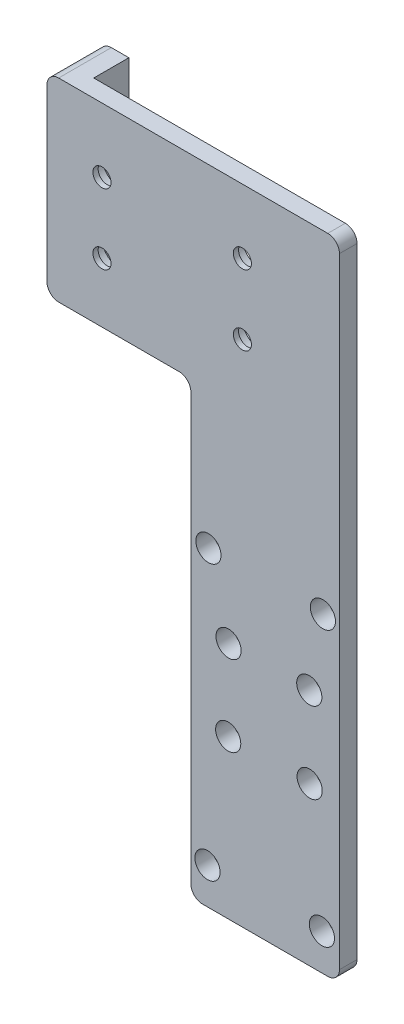
SolidWorks part; units mm, degrees
material "ABS"
ref_plane "Plan de face" through (0, 0, 0) normal (0, 0, 1) x (1, 0, 0)
ref_plane "Plan de dessus" through (0, 0, 0) normal (0, 1, 0) x (1, 0, 0)
ref_plane "Plan de droite" through (0, 0, 0) normal (1, 0, 0) x (0, 0, -1)
sketch "Esquisse1" plane through (0, 0, 0) normal (0, 0, 1) x (1, 0, 0)
  line L1 (0, 0) -> (26.6382, 0)
  line L2 (1.2382, -33.1762) -> (1.2382, -109.993)
  line L3 (1.2382, -109.993) -> (26.6382, -109.993)
  line L4 (26.6382, 0) -> (26.6382, -109.993)
  line L9 (1.2382, -33.1762) -> (-23.3618, -33.1762)
  line L11 (0, 0) -> (-23.3618, 0)
  line L12 (-23.3618, -33.1762) -> (-23.3618, 0)
  point P4 (-23.3618, -16.5881)
  dimension "D1" = 110
  dimension "D2" = 25.4
  dimension "D3" = 50
extrude "Boss.-Extru.1" add sketch "Esquisse1" along normal blind 3
hole_wizard "Dégagement #61" positions "Esquisse3" profile "Esquisse4" hole size "#6" standard "Ansi Inch" end condition up to next
sketch "Esquisse3" plane through (0, 0, 3) normal (0, 0, 1) x (1, 0, 0)
  line L0 (26.6382, -109.993) -> (26.6382, 0) construction
  line L1 (1.2382, -109.993) -> (26.6382, -109.993) construction
  point P0 (21.4763, -69.193)
  point P2 (7.6763, -69.193)
  point P4 (7.6172, -82.993)
  point P6 (21.5382, -82.993)
  dimension "D1" = 19.558
  dimension "D2" = 19.56
  dimension "D3" = 13.8
  dimension "D4" = 13.8
  dimension "D5" = 13.8
  dimension "D6" = 27
  dimension "D7" = 5.1
  dimension "D8" = 27
sketch "Esquisse4" plane through (21.4763, -69.193, 3) normal (1, 0, 0) x (0, -1, 0)
  line L0 (0, 0) -> (0, 3)
  line L1 (0, 3) -> (2.1526, 3)
  line L2 (2.1526, 3) -> (2.1526, 0)
  line L5 (2.1526, 0) -> (0, 0)
  line L11 (0, -6.35) -> (0, 107.95) construction
  dimension "Diamètre du perçage jusqu'au prochain" = 4.3053
  dimension "Profondeur du perçage jusqu'au prochain" = 3
hole_wizard "Chambrage pour vis à tête ronde bombée M2.51" positions "Esquisse5" profile "Esquisse6" counterbore size "M2.5" standard "Ansi Metric" end condition up to next
sketch "Esquisse5" plane through (0, 0, 0) normal (0, 0, -1) x (-1, 0, 0)
  line L0 (-26.6382, 0) -> (23.3618, 0) construction
  line L1 (23.3618, 0) -> (23.3618, -33.1762) construction
  point P0 (13.9618, -23)
  point P2 (13.9618, -11)
  point P4 (-10.0382, -11)
  point P6 (-10.0382, -23)
  dimension "D1" = 11
  dimension "D2" = 9.4
  dimension "D3" = 12
  dimension "D4" = 24
  dimension "D5" = 12
  dimension "D6" = 24
  dimension "D7" = 11
  dimension "D8" = 9.4
sketch "Esquisse6" plane through (-13.9618, -23, 0) normal (1, 0, 0) x (0, 1, 0)
  line L0 (0, 0) -> (0, 3)
  line L1 (0, 3) -> (1.55, 3)
  line L3 (1.55, 3) -> (1.55, 2.1)
  line L4 (1.55, 2.1) -> (3, 2.1)
  line L5 (3, 2.1) -> (3, 0)
  line L7 (3, 0) -> (0, 0)
  line L11 (0, -6.35) -> (0, 107.95) construction
  dimension "Diamètre du perçage jusqu'au prochain" = 3.1
  dimension "Profondeur du perçage jusqu'au prochain" = 3
  dimension "Diamètre du chambrage" = 6
  dimension "Profondeur du chambrage" = 2.1
sketch "Esquisse7" plane through (0, 0, 0) normal (0, 0, -1) x (-1, 0, 0)
  line L0 (-11.6382, -63.1762) -> (-11.6382, -33.1762)
  line L2 (-16.6382, -28.1762) -> (-16.6382, -63.1762)
  line L3 (-16.6382, -63.1762) -> (-11.6382, -63.1762)
  line L9 (-11.6382, -33.1762) -> (23.3618, -33.1762)
  line L11 (-16.6382, -28.1762) -> (18.3618, -28.1762)
  line L14 (23.3618, -33.1762) -> (23.3618, 0)
  line L15 (23.3618, 0) -> (18.3618, 0)
  line L16 (18.3618, -28.1762) -> (18.3618, 0)
  line L21 (-16.6382, -89.993) -> (-11.6382, -89.993)
  line L22 (-16.6382, -89.993) -> (-16.6382, -109.993)
  line L23 (-16.6382, -109.993) -> (-11.6382, -109.993)
  line L24 (-11.6382, -89.993) -> (-11.6382, -109.993)
  line L29 (-26.6382, -109.993) -> (-26.6382, 0) construction
  line L30 (-1.2382, -109.993) -> (-26.6382, -109.993) construction
  dimension "D1" = 5
  dimension "D2" = 5
  dimension "D3" = 5
  dimension "D4" = 10
  dimension "D5" = 5
  dimension "D6" = 35
  dimension "D7" = 20
  dimension "D8" = 10
  dimension "D9" = 0
extrude "Boss.-Extru.2" add sketch "Esquisse7" along normal blind 6
sketch "Esquisse8" plane through (11.6382, 0, 0) normal (-1, 0, 0) x (0, 0, 1)
  line L0 (-6, -63.1762) -> (-6, -33.1762) construction
  line L1 (-4, -46.1762) -> (-2, -46.1762)
  line L2 (-4, -46.1762) -> (-4, -52.1762)
  line L3 (-4, -52.1762) -> (-2, -52.1762)
  line L4 (-2, -46.1762) -> (-2, -52.1762)
  line L5 (-6, -63.1762) -> (0, -63.1762) construction
  dimension "D1" = 6
  dimension "D2" = 2
  dimension "D3" = 2
  dimension "D4" = 11
extrude "Enlèv. mat.-Extru.1" cut sketch "Esquisse8" against normal up to next
sketch "Esquisse9" plane through (0, -33.1762, 0) normal (0, -1, 0) x (1, 0, 0)
  line L0 (11.6382, -6) -> (-23.3618, -6) construction
  line L1 (-0.3618, -4) -> (-6.3618, -4)
  line L2 (-0.3618, -4) -> (-0.3618, -2)
  line L3 (-0.3618, -2) -> (-6.3618, -2)
  line L4 (-6.3618, -4) -> (-6.3618, -2)
  line L5 (11.6382, -6) -> (11.6382, 0) construction
  dimension "D1" = 6
  dimension "D2" = 2
  dimension "D3" = 2
  dimension "D4" = 12
extrude "Enlèv. mat.-Extru.2" cut sketch "Esquisse9" against normal up to next
sketch "Esquisse10" plane through (-23.3618, 0, 0) normal (-1, 0, 0) x (0, 0, 1)
  line L0 (-6, -33.1762) -> (-6, 0) construction
  line L1 (-4, -12.1762) -> (-2, -12.1762)
  line L2 (-4, -12.1762) -> (-4, -18.1762)
  line L3 (-4, -18.1762) -> (-2, -18.1762)
  line L4 (-2, -12.1762) -> (-2, -18.1762)
  line L5 (3, -33.1762) -> (-6, -33.1762) construction
  dimension "D1" = 6
  dimension "D2" = 2
  dimension "D3" = 2
  dimension "D4" = 15
extrude "Enlèv. mat.-Extru.3" cut sketch "Esquisse10" against normal up to next
fillet "Congé1" radius 2 9 edges at (-18.3618, -28.1762, -3) (16.6382, -28.1762, -3) (11.6382, -33.1762, -3) (1.2382, -33.1762, 1.5) (26.6382, -109.993, 1.5) (1.2382, -109.993, 1.5) (-23.3618, 0, -1.5) (26.6382, 0, 1.5) (-23.3618, -33.1762, -1.5)
hole_wizard "Dégagement #65" positions "Esquisse11" profile "Esquisse12" hole size "#6" standard "Ansi Inch" end condition through all
sketch "Esquisse11" plane through (0, 0, 0) normal (0, 0, -1) x (-1, 0, 0)
  line L0 (-26.6382, -107.993) -> (-26.6382, -2) construction
  line L1 (-16.6382, -109.993) -> (-24.6382, -109.993) construction
  line L2 (-3.2382, -109.993) -> (-11.6382, -109.993) construction
  point P0 (-23.6382, -103.793)
  point P2 (-4.0782, -103.793)
  dimension "D1" = 3
  dimension "D2" = 6.2
  dimension "D3" = 19.56
  dimension "D4" = 6.2
sketch "Esquisse12" plane through (23.6382, -103.793, 0) normal (1, 0, 0) x (0, 1, 0)
  line L0 (0, 0) -> (0, 3)
  line L1 (0, 3) -> (2.1526, 3)
  line L2 (2.1526, 3) -> (2.1526, 0)
  line L5 (2.1526, 0) -> (0, 0)
  line L11 (0, -6.35) -> (0, 107.95) construction
  dimension "Diamètre du perçage jusqu'au prochain" = 4.3053
  dimension "Profondeur du perçage jusqu'au prochain" = 3
hole_wizard "Dégagement #64" positions "Esquisse13" profile "Esquisse14" hole size "#6" standard "Ansi Inch" end condition up to next
sketch "Esquisse13" plane through (0, 0, 0) normal (0, 0, -1) x (-1, 0, 0)
  line L0 (-1.2382, -35.1762) -> (-1.2382, -107.993) construction
  line L1 (-16.6382, -109.993) -> (-24.6382, -109.993) construction
  line L2 (-3.2382, -109.993) -> (-11.6382, -109.993) construction
  point P0 (-23.7982, -56.793)
  point P2 (-4.2382, -56.793)
  dimension "D1" = 3
  dimension "D2" = 19.56
  dimension "D3" = 53.2
  dimension "D4" = 53.2
sketch "Esquisse14" plane through (23.7982, -56.793, 0) normal (1, 0, 0) x (0, 1, 0)
  line L0 (0, 0) -> (0, 3)
  line L1 (0, 3) -> (2.1526, 3)
  line L2 (2.1526, 3) -> (2.1526, 0)
  line L5 (2.1526, 0) -> (0, 0)
  line L11 (0, -6.35) -> (0, 107.95) construction
  dimension "Diamètre du perçage jusqu'au prochain" = 4.3053
  dimension "Profondeur du perçage jusqu'au prochain" = 3
